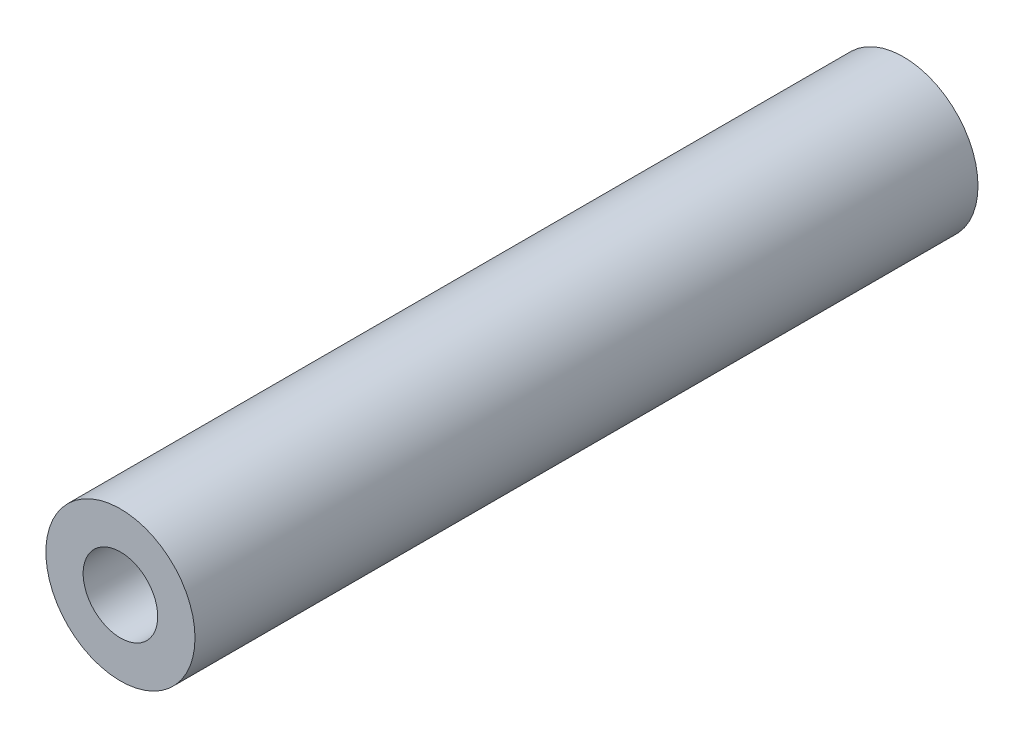
SolidWorks part; units mm, degrees
material "ABS"
ref_plane "Front Plane" through (0, 0, 0) normal (0, 0, 1) x (1, 0, 0)
ref_plane "Top Plane" through (0, 0, 0) normal (0, 1, 0) x (1, 0, 0)
ref_plane "Right Plane" through (0, 0, 0) normal (1, 0, 0) x (0, 0, -1)
sketch "Sketch1" plane through (0, 0, 0) normal (0, 0, 1) x (1, 0, 0)
  circle A0 centre (0, 0) radius 6.35
  circle A1 centre (0, 0) radius 3.175
  dimension "D1" = 6.35
  dimension "D2" = 12.7
extrude "Boss-Extrude1" add sketch "Sketch1" along normal blind 66.675
